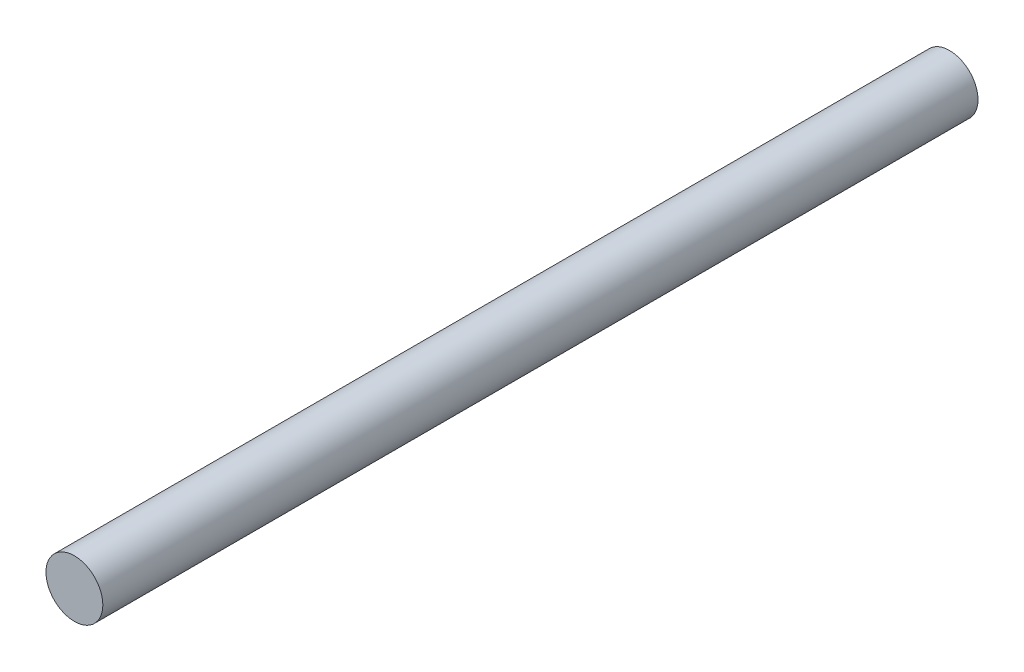
SolidWorks part; units mm, degrees
material "201 Annealed Stainless Steel (SS)"
ref_plane "Front Plane" through (0, 0, 0) normal (0, 0, 1) x (1, 0, 0)
ref_plane "Top Plane" through (0, 0, 0) normal (0, 1, 0) x (1, 0, 0)
ref_plane "Right Plane" through (0, 0, 0) normal (1, 0, 0) x (0, 0, -1)
sketch "Sketch1" plane through (0, 0, 0) normal (0, 0, 1) x (1, 0, 0)
  circle A0 centre (0, 0) radius 3.25
  dimension "D1" = 6.5
extrude "Boss-Extrude1" add sketch "Sketch1" along normal blind 100
